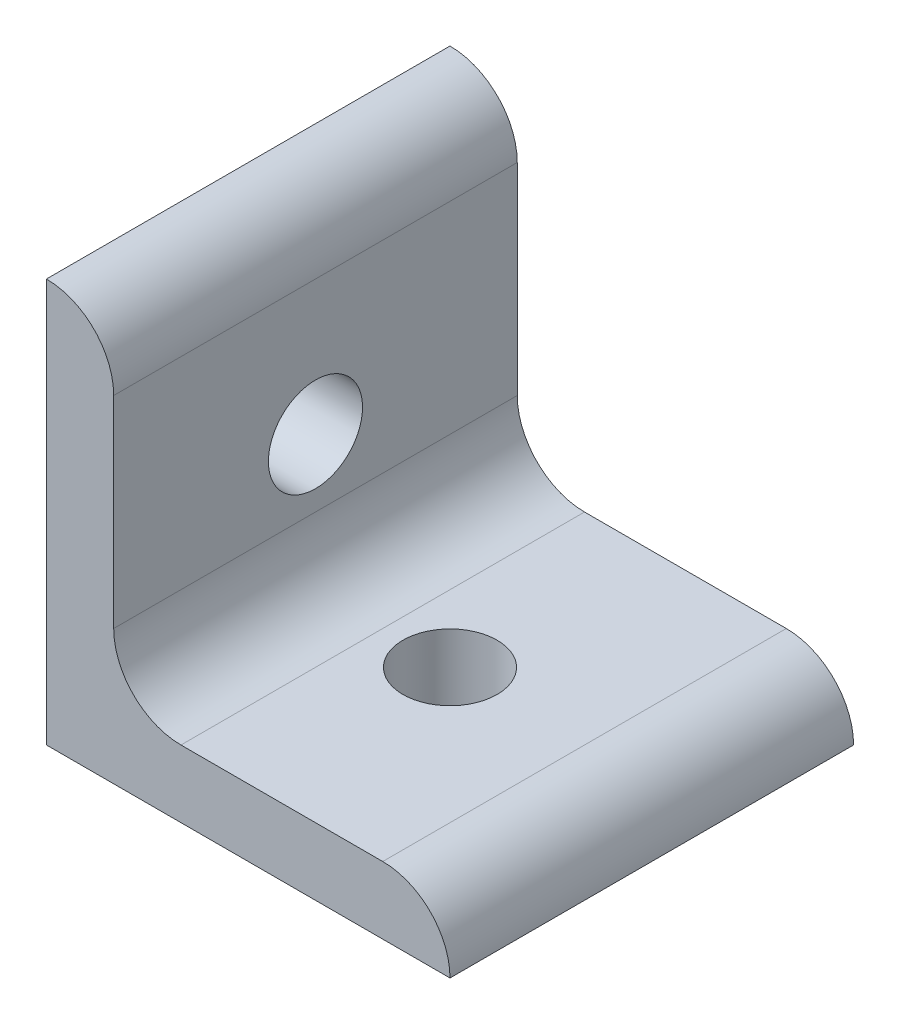
SolidWorks part; units mm, degrees
ref_plane "Front Plane" through (0, 0, 0) normal (0, 0, 1) x (1, 0, 0)
ref_plane "Top Plane" through (0, 0, 0) normal (0, 1, 0) x (1, 0, 0)
ref_plane "Right Plane" through (0, 0, 0) normal (1, 0, 0) x (0, 0, -1)
sketch "Sketch1" plane through (0, 0, 0) normal (0, 0, 1) x (1, 0, 0)
  line L0 (0, 0) -> (0, 30)
  line L1 (5, 25) -> (5, 30) construction
  line L2 (5, 25) -> (5, 10)
  line L3 (10, 5) -> (25, 5)
  line L4 (5, 30) -> (0, 30) construction
  line L5 (30, 0) -> (0, 0)
  line L6 (25, 5) -> (30, 5) construction
  line L7 (30, 5) -> (30, 0) construction
  arc A0 (5, 25) -> (0, 30) centre (0, 25) ccw
  arc A1 (30, 0) -> (25, 5) centre (25, 0) ccw
  arc A2 (5, 10) -> (10, 5) centre (10, 10) ccw
  point P10 (5, 27.5)
  dimension "E" = 5
  dimension "D" = 5
  dimension "C" = 30
  dimension "B" = 30
extrude "Boss-Extrude1" add sketch "Sketch1" along normal mid plane 30
sketch "Sketch2" plane through (0, 0, 0) normal (0, 1, 0) x (1, 0, 0)
  line L0 (0, 0) -> (15, 0) construction
  circle A0 centre (15, 0) radius 3.5
  dimension "D1" = 15
  dimension "E" = 7
extrude "Cut-Extrude1" cut sketch "Sketch2" along normal through all
sketch "Sketch3" plane through (0, 0, 0) normal (1, 0, 0) x (0, 0, -1)
  line L0 (0, 0) -> (0, 15) construction
  circle A0 centre (0, 15) radius 3.5
  dimension "D1" = 15
  dimension "E" = 7
extrude "Cut-Extrude2" cut sketch "Sketch3" along normal through all
equation "\"E@Sketch3\" = \"E@Sketch2\""
equation "\"D1@Sketch3\" = \"D1@Sketch2\""
